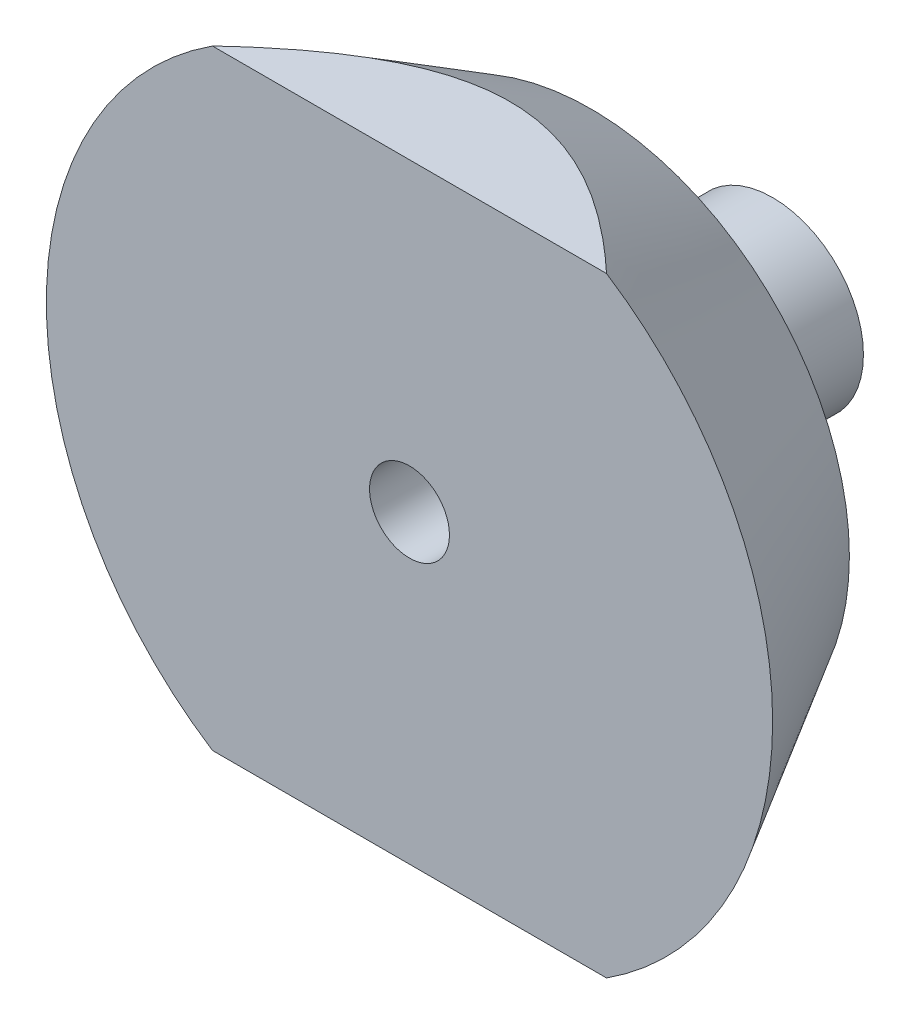
SolidWorks part; units mm, degrees
ref_plane "Front Plane" through (0, 0, 0) normal (0, 0, 1) x (1, 0, 0)
ref_plane "Top Plane" through (0, 0, 0) normal (0, 1, 0) x (1, 0, 0)
ref_plane "Right Plane" through (0, 0, 0) normal (1, 0, 0) x (0, 0, -1)
sketch "Sketch1" plane through (0, 0, 0) normal (0, 0, 1) x (1, 0, 0)
  circle A0 centre (0, 0) radius 50
  dimension "D1" = 100
extrude "Extrude1" add sketch "Sketch1" against normal blind 25 draft 30
sketch "Sketch2" plane through (0, 0, -25) normal (0, 0, -1) x (-1, 0, 0)
  circle A0 centre (0, 0) radius 12.5
  dimension "D1" = 25
extrude "Extrude2" add sketch "Sketch2" along normal blind 25
sketch "Sketch3" plane through (0, 0, -50) normal (0, 0, -1) x (-1, 0, 0)
  circle A0 centre (0, 0) radius 8
  dimension "D1" = 16
extrude "Cut-Extrude1" cut sketch "Sketch3" against normal blind 16
hole_wizard "Ø11.0 (11) Diameter Hole1" positions "Sketch6" profile "Sketch5" hole size "Ø11.0" standard "ANSI Metric" end condition through all
sketch "Sketch6" plane through (0, 0, 0) normal (0, 0, 1) x (1, 0, 0)
  point P0 (0, 0)
sketch "Sketch5" plane through (0, 0, 0) normal (1, 0, 0) x (0, -1, 0)
  line L0 (0, 0) -> (0, 50)
  line L1 (0, 50) -> (5.5, 50)
  line L2 (5.5, 50) -> (5.5, 0)
  line L5 (5.5, 0) -> (0, 0)
  line L11 (0, -6.35) -> (0, 107.95) construction
  dimension "Thru Hole Dia." = 11
  dimension "Thru Hole Depth" = 50
sketch "Sketch7" plane through (0, 0, -25) normal (0, 0, -1) x (-1, 0, 0)
  line L0 (-55, 42) -> (60, 42)
  line L1 (60, 42) -> (60, -42)
  line L2 (60, -42) -> (-55, -42)
  line L3 (-55, -42) -> (-55, -67)
  line L4 (-55, -67) -> (80, -67)
  line L5 (80, -67) -> (80, 67)
  line L6 (80, 67) -> (-55, 67)
  line L7 (-55, 67) -> (-55, 42)
  dimension "D1" = 42
  dimension "D2" = 25
  dimension "D3" = 25
  dimension "D4" = 42
  dimension "D5" = 60
  dimension "D6" = 20
  dimension "D7" = 135
extrude "Cut-Extrude2" cut sketch "Sketch7" against normal through all
